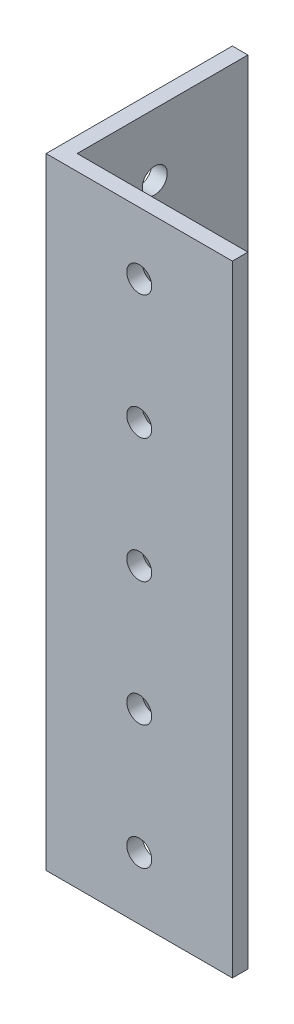
SolidWorks part; units mm, degrees
ref_plane "Front Plane" through (0, 0, 0) normal (0, 0, 1) x (1, 0, 0)
ref_plane "Top Plane" through (0, 0, 0) normal (0, 1, 0) x (1, 0, 0)
ref_plane "Right Plane" through (0, 0, 0) normal (1, 0, 0) x (0, 0, -1)
sketch "Sketch2" plane through (0, 0, 0) normal (0, 1, 0) x (1, 0, 0)
  line L1 (-33.3198, -0.4952) -> (4.7802, -0.4952)
  line L2 (-33.3198, -0.4952) -> (-33.3198, 37.6048)
  line L3 (-33.3198, 37.6048) -> (4.7802, 37.6048)
  line L4 (4.7802, -0.4952) -> (4.7802, 37.6048)
  line L5 (-33.3198, -0.4952) -> (4.7802, 37.6048) construction
  line L6 (-33.3198, 37.6048) -> (4.7802, -0.4952) construction
  line L7 (-30.1448, 2.6798) -> (4.7802, 2.6798)
  line L8 (-30.1448, 2.6798) -> (-30.1448, 37.6048)
  line L9 (-30.1448, 37.6048) -> (4.7802, 37.6048)
  line L10 (4.7802, 2.6798) -> (4.7802, 37.6048)
  line L11 (-30.1448, 2.6798) -> (4.7802, 37.6048) construction
  line L12 (-30.1448, 37.6048) -> (4.7802, 2.6798) construction
  point P0 (-14.2698, 18.5548)
  point P5 (-12.6823, 20.1423)
  dimension "D1" = 38.1
  dimension "D2" = 38.1
  dimension "D3" = 34.925
  dimension "D4" = 34.925
  dimension "D5" = 3.175
  dimension "D6" = 3.175
extrude "Boss-Extrude1" add sketch "Sketch2" along normal blind 127 contours L7 L8 L3 L2 L1 L4
sketch "Sketch3" plane through (-30.1448, 0, 0) normal (1, 0, 0) x (0, 0, -1)
  line L0 (2.6798, 0) -> (37.6048, 0) construction
  line L1 (37.6048, 127) -> (37.6048, 0) construction
  circle A0 centre (18.5548, 12.7) radius 2.5527
  dimension "D1" = 5.1054
  dimension "D2" = 12.7
  dimension "D3" = 19.05
extrude "Cut-Extrude1" cut sketch "Sketch3" against normal through all
pattern_linear "LPattern1" count 5 spacing 25.4 along (0, 1, 0) of "Cut-Extrude1"
sketch "Sketch4" plane through (0, 0, -2.6798) normal (0, 0, -1) x (-1, 0, 0)
  line L0 (30.1448, 0) -> (-4.7802, 0) construction
  line L1 (-4.7802, 127) -> (-4.7802, 0) construction
  circle A0 centre (14.2698, 12.7) radius 2.5527
  dimension "D1" = 5.1054
  dimension "D2" = 12.7
  dimension "D3" = 19.05
extrude "Cut-Extrude2" cut sketch "Sketch4" against normal through all
pattern_linear "LPattern2" count 5 spacing 25.4 along (0, 1, 0) of "Cut-Extrude2"
